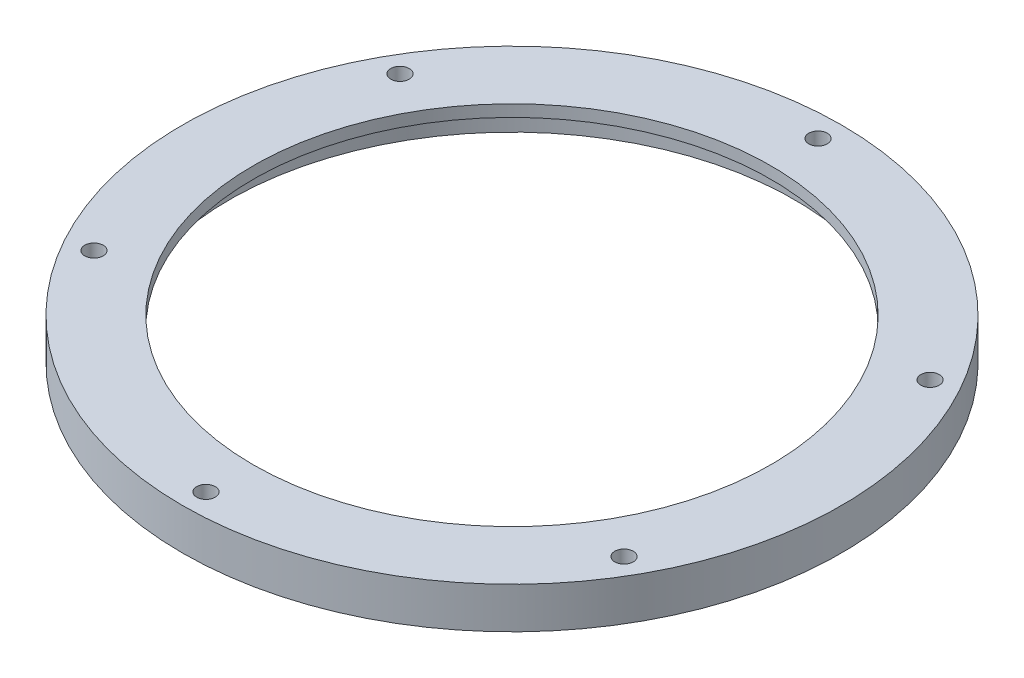
SolidWorks part; units mm, degrees
ref_plane "Front Plane" through (0, 0, 0) normal (0, 0, 1) x (1, 0, 0)
ref_plane "Top Plane" through (0, 0, 0) normal (0, 1, 0) x (1, 0, 0)
ref_plane "Right Plane" through (0, 0, 0) normal (1, 0, 0) x (0, 0, -1)
sketch "Sketch1" plane through (0, 0, 0) normal (0, 1, 0) x (1, 0, 0)
  circle A0 centre (0, 0) radius 88.9
  circle A1 centre (0, 0) radius 76.2
  dimension "D1" = 152.4
  dimension "D2" = 177.8
extrude "Boss-Extrude1" add sketch "Sketch1" along normal blind 7.9375
sketch "Sketch2" plane through (0, 7.9375, 0) normal (0, 1, 0) x (1, 0, 0)
  circle A0 centre (0, 0) radius 88.9
  circle A1 centre (0, 0) radius 69.85
  circle A2 centre (0, 0) radius 88.9 construction
  circle A3 centre (0, 0) radius 76.2 construction
  dimension "D1" = 6.35
extrude "Boss-Extrude2" add sketch "Sketch2" along normal blind 3.175
sketch "Sketch3" plane through (0, 11.1125, 0) normal (0, 1, 0) x (1, 0, 0)
  line L0 (0, 76.2) -> (0, 88.9) construction
  circle A0 centre (0, 0) radius 76.2 construction
  circle A1 centre (0, 0) radius 88.9 construction
  circle A2 centre (0, 82.55) radius 2.5
  dimension "D1" = 152.4
  dimension "D2" = 5
extrude "Cut-Extrude1" cut sketch "Sketch3" against normal through all
pattern_circular "CirPattern1" count 6 over 360 about axis through (0, 0, 0) along (0, 1, 0) of "Cut-Extrude1"
